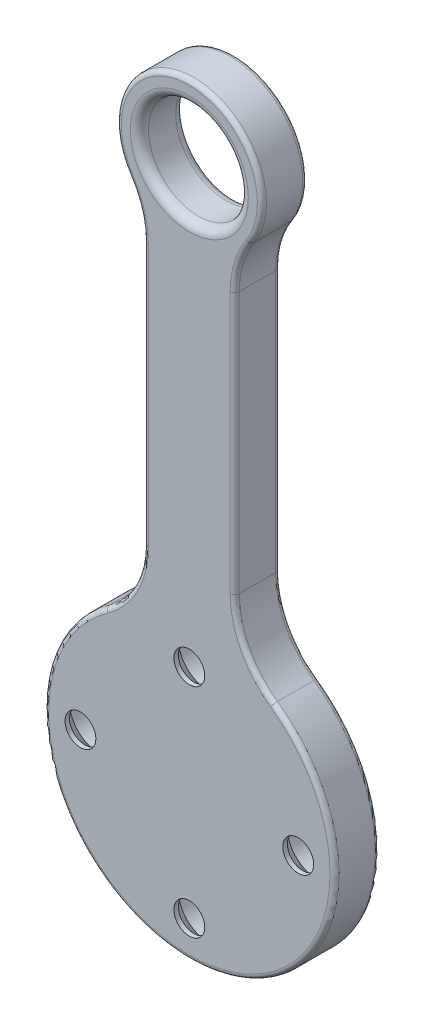
SolidWorks part; units mm, degrees
ref_plane "Front Plane" through (0, 0, 0) normal (0, 0, 1) x (1, 0, 0)
ref_plane "Top Plane" through (0, 0, 0) normal (0, 1, 0) x (1, 0, 0)
ref_plane "Right Plane" through (0, 0, 0) normal (1, 0, 0) x (0, 0, -1)
ref_plane "Plane1" through (0, 0, 5) normal (0, 0, 1) x (1, 0, 0)
sketch "Sketch1" plane through (0, 0, 5) normal (0, 0, 1) x (1, 0, 0)
  line L0 (-5, 53.755) -> (-5, 13.0767)
  line L1 (5, 13.0767) -> (5, 53.755)
  line L2 (-5, 39.7889) -> (5, 39.7889) construction
  arc A0 (-5, 13.0767) -> (5, 13.0767) centre (0, 0) ccw
  arc A1 (5, 53.755) -> (-5, 53.755) centre (0, 60) ccw
  point P6 (0, 39.7889)
  dimension "D2" = 14
  dimension "D3" = 8
  dimension "D1" = 60
  dimension "D4" = 10
extrude "Boss-Extrude1" add sketch "Sketch1" against normal blind 5
ref_plane "Plane2" through (0, 60, 0) normal (0, -1, 0) x (1, 0, 0)
sketch "Sketch2" plane through (0, 60, 0) normal (0, -1, 0) x (1, 0, 0)
  line L0 (3.5, 5) -> (0, 5)
  line L1 (0, 5) -> (0, 0)
  line L2 (0, 0) -> (4.3, 0)
  line L3 (4.3, 0) -> (2.5, 1.8)
  line L4 (2.5, 1.8) -> (2.5, 2)
  line L5 (2.5, 2) -> (3.5, 2)
  line L6 (3.5, 2) -> (3.5, 5)
  line L7 (0, 5) -> (0, 0) construction
revolve "Cut-Revolve1" cut sketch "Sketch2" angle 360 about L7
sketch "Sketch8" plane through (0, 0, 0) normal (0, 0, -1) x (-1, 0, 0)
  circle A0 centre (0, 0) radius 16
  dimension "D1" = 32
extrude "Boss-Extrude2" add sketch "Sketch8" against normal up to vertex (5 mm away)
hole_wizard "CBORE for M3 Hex Head Machine Screw0" positions "Sketch4" profile "Sketch3" counterbore size "M3" standard "ANSI Metric" end condition through all
sketch "Sketch4" plane through (0, 0, 0) normal (0, 0, -1) x (-1, 0, 0)
  line L0 (12, 0) -> (0, 0) construction
  line L1 (0, 0) -> (-12, 0) construction
  line L3 (0, 12) -> (0, 0) construction
  line L4 (0, 0) -> (0, -12) construction
  point P0 (0, 12)
  point P1 (12, 0)
  point P2 (-12, 0)
  point P3 (0, -12)
  dimension "D1" = 12
sketch "Sketch3" plane through (0, 12, 0) normal (1, 0, 0) x (0, 1, 0)
  line L0 (0, 0) -> (0, 5)
  line L1 (0, 5) -> (1.7, 5)
  line L3 (1.7, 5) -> (1.7, 3)
  line L4 (1.7, 3) -> (3.25, 3)
  line L5 (3.25, 3) -> (3.25, 0)
  line L7 (3.25, 0) -> (0, 0)
  line L11 (0, -6.35) -> (0, 107.95) construction
  dimension "Thru Hole Dia." = 3.4
  dimension "Thru Hole Depth" = 5
  dimension "C'Bore Dia." = 6.5
  dimension "C'Bore Depth" = 3
fillet "Fillet1" radius 10 4 edges at (-5, 53.755, 2.5) (5, 53.755, 2.5) (5, 15.1987, 2.5) (-5, 15.1987, 2.5)
sketch "Sketch7" plane through (0, 0, 0) normal (0, 0, -1) x (-1, 0, 0)
  circle A0 centre (0, 60) radius 5.5
  circle A1 centre (0, 60) radius 4.3 construction
  dimension "D1" = 11
extrude "Cut-Extrude1" cut sketch "Sketch7" against normal through all
fillet "Fillet2" radius 1 2 edges at (-5.5, 60, 5) (-5.5, 60, 0)
fillet "Fillet3" radius 0.5 16 edges at (6.1205, 16.6374, 0) (6.1205, 16.6374, 5) (5, 35.6434, 5) (5, 35.6434, 0) (5.4257, 52.9369, 0) (5.4257, 52.9369, 5) (0, 68, 0) (0, 68, 5) (-5.4257, 52.9369, 0) (-5.4257, 52.9369, 5) (-5, 35.6434, 0) (-5, 35.6434, 5) (-6.1205, 16.6374, 5) (-6.1205, 16.6374, 0) (0, -16, 0) (0, -16, 5)
chamfer "Chamfer1" distance 1.5 angle 45 4 edges at (-1.7, -12, 3) (10.3, 0, 3) (-13.7, 0, 3) (-1.7, 12, 3)
